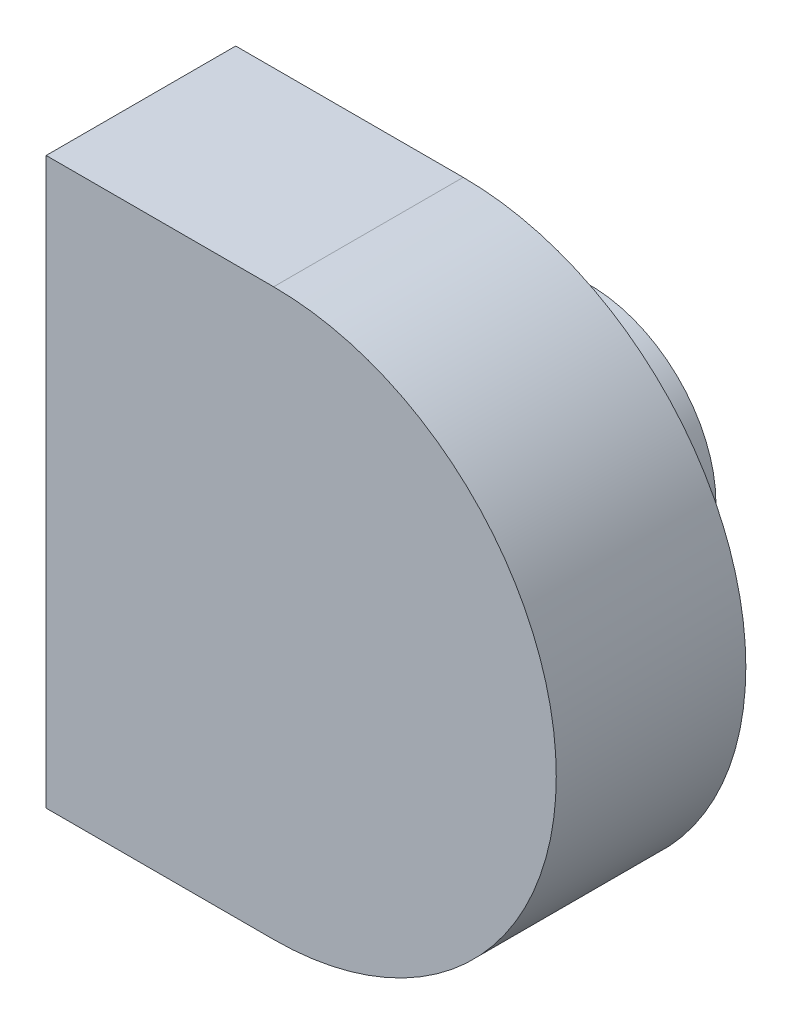
SolidWorks part; units mm, degrees
ref_plane "前视基准面" through (0, 0, 0) normal (0, 0, 1) x (1, 0, 0)
ref_plane "上视基准面" through (0, 0, 0) normal (0, 1, 0) x (1, 0, 0)
ref_plane "右视基准面" through (0, 0, 0) normal (1, 0, 0) x (0, 0, -1)
other "Configuration Table"
sketch "草图1" plane through (0, 0, 0) normal (0, 0, 1) x (1, 0, 0)
  line L1 (0, 0) -> (189.06, 0)
  line L2 (0, 0) -> (0, 44.73)
  line L3 (0, 44.73) -> (189.06, 44.73)
  line L4 (189.06, 0) -> (189.06, 44.73)
  dimension "D1" = 189.06
  dimension "D2" = 44.73
extrude "凸台-拉伸1" add sketch "草图1" along normal blind 15
sketch "草图2" plane through (0, 0, 0) normal (0, 0, 1) x (1, 0, 0)
  line L0 (0, 22.365) -> (6, 22.365) construction
  line L1 (0, 44.73) -> (0, 0) construction
  line L2 (49.87, 22.365) -> (49.87, 38.3624) construction
  line L3 (49.87, 22.365) -> (49.87, -29.0061) construction
  line L4 (6, 22.365) -> (91.74, 22.365) construction
  line L5 (91.74, 22.365) -> (93.74, 22.365) construction
  line L6 (189.06, 44.73) -> (0, 44.73) construction
  arc A2 (0.0194, 23.7552) -> (2.9047, 39.1362) centre (49.87, 22.365) cw
  arc A12 (92.412, 17.0724) -> (89.7396, 6.609) centre (49.87, 22.365) cw
  arc A13 (92.0308, 30.1305) -> (92.6094, 19.0214) centre (49.87, 22.365) cw
  arc A14 (7.0167, 23.56) -> (9.4969, 36.7821) centre (49.87, 22.365) cw
  arc A15 (11.5101, 3.2246) -> (7.5633, 15.4382) centre (49.87, 22.365) cw
  circle A16 centre (9.0186, 9.365) radius 1
  circle A17 centre (7, 22.365) radius 1
  circle A18 centre (9.0186, 35.365) radius 1
  circle A19 centre (90.7214, 9.365) radius 1
  circle A20 centre (90.7214, 35.365) radius 1
  circle A21 centre (92.74, 22.365) radius 1
  point P52 (39.3691, 16.6488)
  dimension "D1" = 42.87
  dimension "D2" = 42.87
  dimension "D4" = 2
  dimension "D5" = 2
  dimension "D6" = 2
  dimension "D7" = 2
  dimension "D8" = 2
  dimension "D9" = 13
  dimension "D10" = 13
  dimension "D11" = 13
  dimension "D3" = 2
  dimension "D14" = 42.87
  dimension "D15" = 42.87
  dimension "D12" = 13
  dimension "D13" = 7
  dimension "D16" = 32.87
  dimension "D17" = 22.365
sketch "草图3" plane through (0, 0, 0) normal (0, 0, -1) x (-1, 0, 0)
  line L0 (0, 22.365) -> (-6, 22.365) construction
  line L1 (0, 22.365) -> (-224.1604, 22.365) construction
  line L2 (-189.06, 44.73) -> (0, 44.73) construction
  line L3 (-18, 32.365) -> (-26.6603, 27.365)
  line L4 (-26.6603, 27.365) -> (-26.6603, 17.365)
  line L5 (-26.6603, 17.365) -> (-18, 12.365)
  line L6 (-18, 12.365) -> (-9.3397, 17.365)
  line L7 (-9.3397, 17.365) -> (-9.3397, 27.365)
  line L8 (-9.3397, 27.365) -> (-18, 32.365)
  line L9 (0, 44.73) -> (0, 0) construction
  circle A0 centre (-18, 22.365) radius 10
  circle A1 centre (-18, 22.365) radius 8.6603 construction
  circle A3 centre (-18, 22.365) radius 18
  point P2 (-18, 22.365)
  dimension "D2" = 20
  dimension "D3" = 18
  dimension "D1" = 22.365
sketch "草图4" plane through (0, 0, 15) normal (0, 0, 1) x (1, 0, 0)
  line L0 (189.06, 44.73) -> (0, 44.73) construction
  line L1 (0, 0) -> (189.06, 0) construction
  line L4 (0, 44.73) -> (0, 0)
  line L5 (0, 0) -> (189.06, 0)
  line L6 (189.06, 0) -> (189.06, 44.73)
  line L7 (189.06, 44.73) -> (0, 44.73)
  line L8 (0, 44.73) -> (0, 0)
  line L9 (18, 0) -> (189.06, 0)
  line L10 (189.06, 0) -> (189.06, 44.73)
  line L11 (189.06, 44.73) -> (18, 44.73)
  arc A2 (18, 0) -> (18, 44.73) centre (18, 22.365) ccw
  circle A3 centre (18, 22.365) radius 18 construction
  line M6 (0, 0) -> (189.06, 0)
  line M7 (189.06, 0) -> (189.06, 44.73)
  line M8 (189.06, 44.73) -> (0, 44.73)
  dimension "D1" = 0
extrude "切除-拉伸4" cut sketch "草图4" against normal up to next contours A2 M6 M7 M8
sketch "草图6" plane through (0, 0, 0) normal (0, 0, -1) x (-1, 0, 0)
  line L3 (0, 44.73) -> (-18, 44.73)
  line L4 (-18, 0) -> (0, 0)
  line L5 (0, 0) -> (0, 44.73)
  line L8 (0, 0) -> (0, 44.73)
  circle A0 centre (-18, 22.365) radius 10 construction
  arc A1 (-18, 44.73) -> (-18, 0) centre (-18, 22.365) ccw
  circle A3 centre (-18, 22.365) radius 10
  dimension "D2" = 20
  dimension "D1" = 0
extrude "凸台-拉伸2" add sketch "草图6" along normal blind 10 contours A3
sketch "草图7" plane through (0, 0, -10) normal (0, 0, -1) x (-1, 0, 0)
  circle A0 centre (-18, 22.365) radius 10 construction
  circle A1 centre (-18, 22.365) radius 10 construction
  circle A2 centre (-18, 22.365) radius 7 construction
  circle A3 centre (-18, 29.365) radius 1
  circle A7 centre (-11, 22.365) radius 1
  circle A8 centre (-18, 15.365) radius 1
  circle A9 centre (-25, 22.365) radius 1
  point P15 (-85.6058, -45.2408)
  dimension "D1" = 14
  dimension "D2" = 2
  dimension "D3" = 4
extrude "切除-拉伸6" cut sketch "草图7" against normal blind 5
sketch "草图8" plane through (0, 0, 0) normal (0, 0, -1) x (-1, 0, 0)
  circle A0 centre (-18, 22.365) radius 10 construction
  circle A1 centre (-18, 22.365) radius 10
  circle A2 centre (-18, 22.365) radius 12
  dimension "D1" = 24
extrude "凸台-拉伸3" add sketch "草图8" along normal blind 2.5
